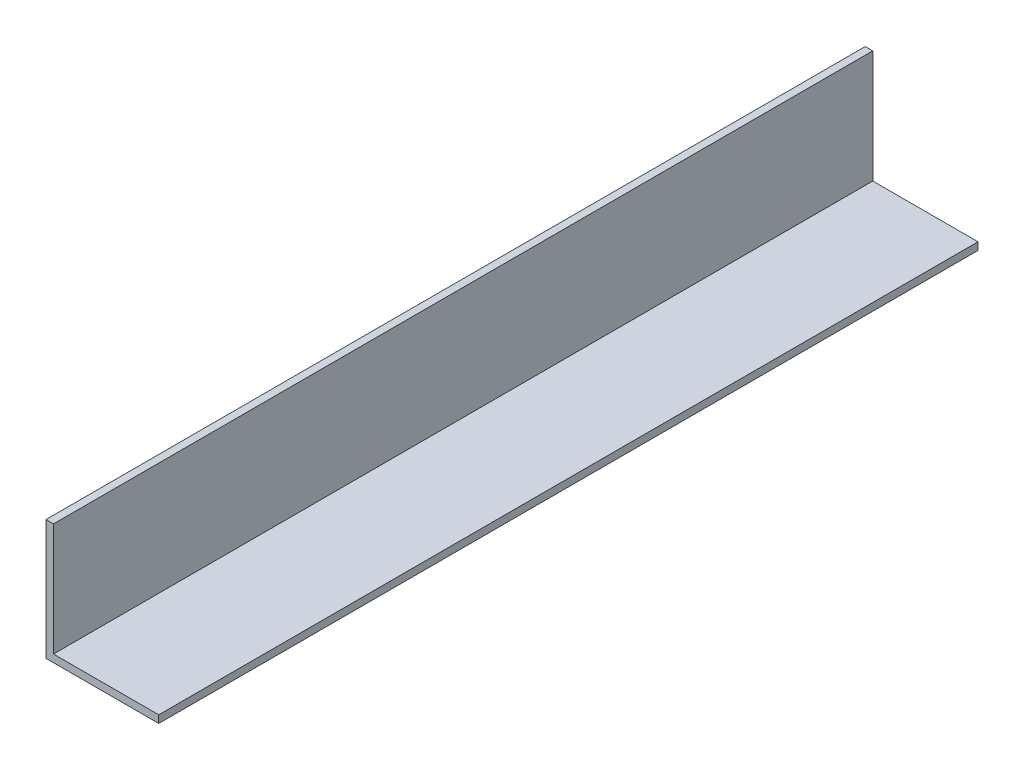
SolidWorks part; units mm, degrees
ref_plane "Front Plane" through (0, 0, 0) normal (0, 0, 1) x (1, 0, 0)
ref_plane "Top Plane" through (0, 0, 0) normal (0, 1, 0) x (1, 0, 0)
ref_plane "Right Plane" through (0, 0, 0) normal (1, 0, 0) x (0, 0, -1)
sketch "Sketch1" plane through (0, 0, 0) normal (0, 0, 1) x (1, 0, 0)
  line L0 (0, 0) -> (0, 32)
  line L1 (0, 32) -> (2, 32)
  line L2 (2, 32) -> (2, 2)
  line L3 (2, 2) -> (30, 2)
  line L4 (30, 2) -> (30, 0)
  line L5 (30, 0) -> (0, 0)
  dimension "D1" = 2
  dimension "D2" = 2
  dimension "D3" = 30
  dimension "D4" = 30
  dimension "D5" = 28
extrude "Boss-Extrude1" add sketch "Sketch1" along normal blind 218
